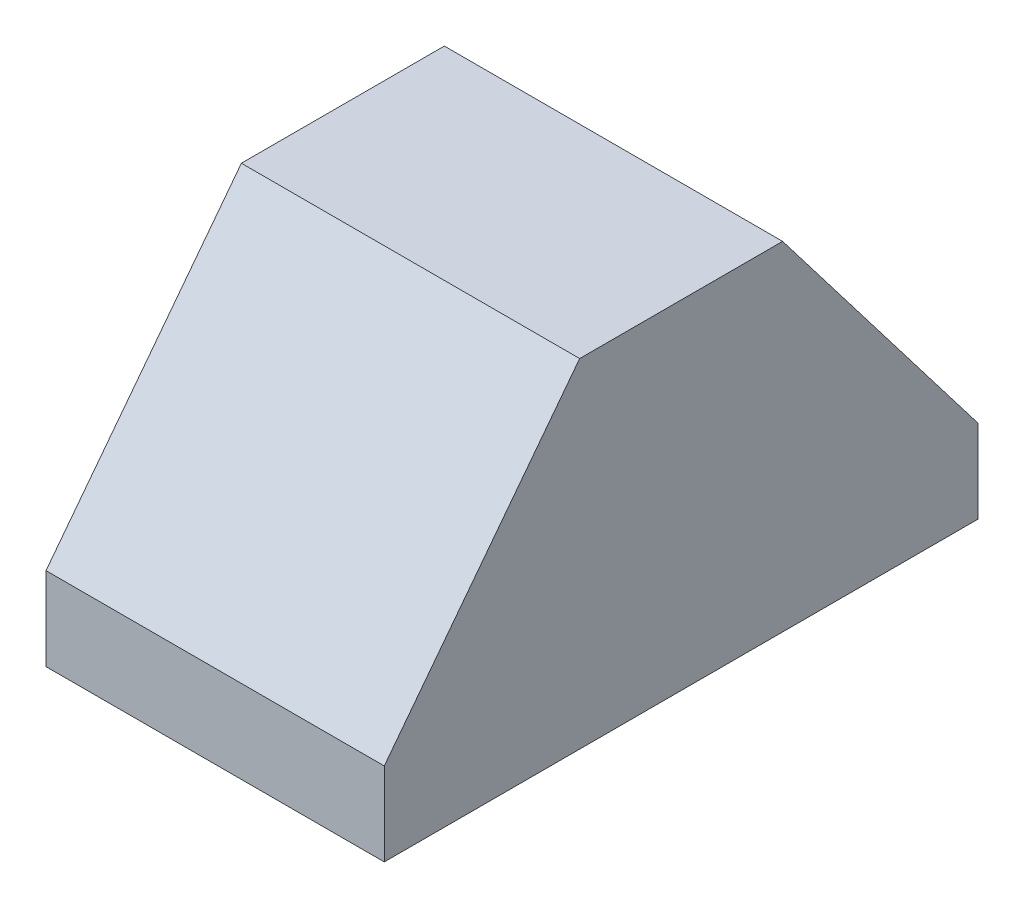
SolidWorks part; units mm, degrees
ref_plane "Front Plane" through (0, 0, 0) normal (0, 0, 1) x (1, 0, 0)
ref_plane "Top Plane" through (0, 0, 0) normal (0, 1, 0) x (1, 0, 0)
ref_plane "Right Plane" through (0, 0, 0) normal (1, 0, 0) x (0, 0, -1)
sketch "Sketch2" plane through (0, 0, 0) normal (1, 0, 0) x (0, 0, -1)
  line L0 (0, 0) -> (87.7587, 0)
  line L1 (87.7587, 0) -> (87.7587, 12.2898)
  line L2 (87.7587, 12.2898) -> (58.8793, 50)
  line L3 (58.8793, 50) -> (28.8793, 50)
  line L4 (28.8793, 50) -> (0, 12.2898)
  line L5 (0, 12.2898) -> (0, 0)
  dimension "D1" = 50
  dimension "D2" = 30
extrude "Boss-Extrude1" add sketch "Sketch2" along normal blind 50
